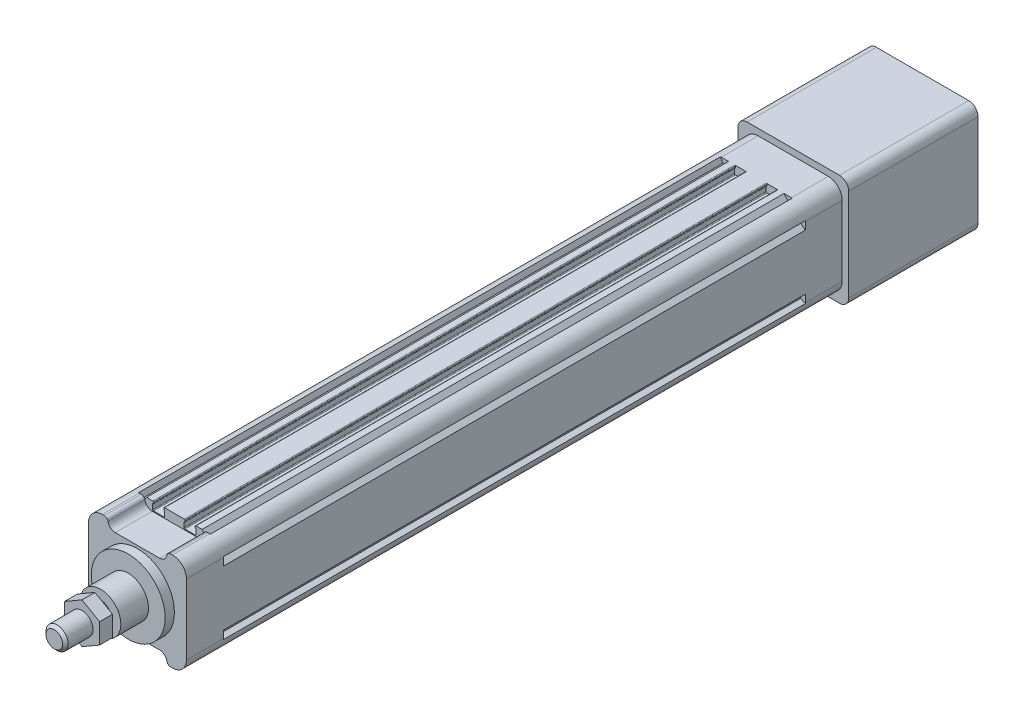
SolidWorks part; units mm, degrees
ref_plane "Front" through (0, 0, 0) normal (0, 0, 1) x (1, 0, 0)
ref_plane "Top" through (0, 0, 0) normal (0, 1, 0) x (1, 0, 0)
ref_plane "Right" through (0, 0, 0) normal (1, 0, 0) x (0, 0, -1)
sketch "草图1" plane through (0, 0, 0) normal (0, 0, 1) x (1, 0, 0)
  line L0 (19.7737, 3) -> (23.3, 3)
  line L1 (23.3, 3) -> (23.3, -3)
  line L2 (23.3, -3) -> (19.7737, -3)
  line L3 (-19.7737, -3) -> (-23.3, -3)
  line L4 (-23.3, -3) -> (-23.3, 3)
  line L5 (-23.3, 3) -> (-19.7737, 3)
  line L6 (-18.2, 24) -> (-19.4434, 26.4869)
  line L7 (-26.4869, 19.4434) -> (-24, 18.2)
  line L8 (-24, 18.2) -> (-24, 17.1)
  line L9 (-24, 17.1) -> (-26.5, 15)
  line L10 (-26.5, 15) -> (-26.5, -15)
  line L11 (-26.5, -15) -> (-24, -17.1)
  line L12 (-24, -17.1) -> (-24, -18.2)
  line L13 (-24, -18.2) -> (-26.4869, -19.4434)
  line L14 (-19.4434, -26.4869) -> (-18.2, -24)
  line L15 (-18.2, -24) -> (-17.1, -24)
  line L16 (-17.1, -24) -> (-15, -26.5)
  line L17 (-15, -26.5) -> (-11.65, -26.5)
  line L18 (-11.25, -26.1) -> (-11.25, -25.6)
  line L19 (-11.65, -25.2) -> (-11.75, -25.2)
  line L20 (-11.75, -25.2) -> (-11.75, -22.4)
  line L21 (-11.35, -22) -> (-5.65, -22)
  line L22 (-5.25, -22.4) -> (-5.25, -25.2)
  line L23 (-5.25, -25.2) -> (-5.35, -25.2)
  line L24 (-5.75, -25.6) -> (-5.75, -26.1)
  line L25 (-5.35, -26.5) -> (5.35, -26.5)
  line L26 (5.75, -26.1) -> (5.75, -25.6)
  line L27 (5.35, -25.2) -> (5.25, -25.2)
  line L28 (5.25, -25.2) -> (5.25, -22.4)
  line L29 (5.65, -22) -> (11.35, -22)
  line L30 (11.75, -22.4) -> (11.75, -25.2)
  line L31 (11.75, -25.2) -> (11.65, -25.2)
  line L32 (11.25, -25.6) -> (11.25, -26.1)
  line L33 (11.65, -26.5) -> (15, -26.5)
  line L34 (15, -26.5) -> (17.1, -24)
  line L35 (17.1, -24) -> (18.2, -24)
  line L36 (18.2, -24) -> (19.4434, -26.4869)
  line L37 (26.4869, -19.4434) -> (24, -18.2)
  line L38 (24, -18.2) -> (24, -17.1)
  line L39 (24, -17.1) -> (26.5, -15)
  line L40 (26.5, -15) -> (26.5, 15)
  line L41 (26.5, 15) -> (24, 17.1)
  line L42 (24, 17.1) -> (24, 18.2)
  line L43 (24, 18.2) -> (26.4869, 19.4434)
  line L44 (19.4434, 26.4869) -> (18.2, 24)
  line L45 (18.2, 24) -> (17.1, 24)
  line L46 (17.1, 24) -> (15, 26.5)
  line L47 (15, 26.5) -> (11.65, 26.5)
  line L48 (11.25, 26.1) -> (11.25, 25.6)
  line L49 (11.65, 25.2) -> (11.75, 25.2)
  line L50 (11.75, 25.2) -> (11.75, 22.4)
  line L51 (11.35, 22) -> (5.65, 22)
  line L52 (5.25, 22.4) -> (5.25, 25.2)
  line L53 (5.25, 25.2) -> (5.35, 25.2)
  line L54 (5.75, 25.6) -> (5.75, 26.1)
  line L55 (5.35, 26.5) -> (-5.35, 26.5)
  line L56 (-5.75, 26.1) -> (-5.75, 25.6)
  line L57 (-5.35, 25.2) -> (-5.25, 25.2)
  line L58 (-5.25, 25.2) -> (-5.25, 22.4)
  line L59 (-5.65, 22) -> (-11.35, 22)
  line L60 (-11.75, 22.4) -> (-11.75, 25.2)
  line L61 (-11.75, 25.2) -> (-11.65, 25.2)
  line L62 (-11.25, 25.6) -> (-11.25, 26.1)
  line L63 (-11.65, 26.5) -> (-15, 26.5)
  line L64 (-15, 26.5) -> (-17.1, 24)
  line L65 (-17.1, 24) -> (-18.2, 24)
  arc A0 (19.7737, 3) -> (-19.7737, 3) centre (0, 0) ccw
  arc A1 (-19.7737, -3) -> (19.7737, -3) centre (0, 0) ccw
  circle A2 centre (19, 19) radius 2.1
  circle A3 centre (19, -19) radius 2.1
  circle A4 centre (-19, -19) radius 2.1
  circle A5 centre (-19, 19) radius 2.1
  arc A6 (-19.4434, 26.4869) -> (-26.4869, 19.4434) centre (-19, 19) ccw
  arc A7 (-26.4869, -19.4434) -> (-19.4434, -26.4869) centre (-19, -19) ccw
  arc A8 (-11.65, -26.5) -> (-11.25, -26.1) centre (-11.65, -26.1) ccw
  arc A9 (-11.25, -25.6) -> (-11.65, -25.2) centre (-11.65, -25.6) ccw
  arc A10 (-11.35, -22) -> (-11.75, -22.4) centre (-11.35, -22.4) ccw
  arc A11 (-5.25, -22.4) -> (-5.65, -22) centre (-5.65, -22.4) ccw
  arc A12 (-5.35, -25.2) -> (-5.75, -25.6) centre (-5.35, -25.6) ccw
  arc A13 (-5.75, -26.1) -> (-5.35, -26.5) centre (-5.35, -26.1) ccw
  arc A14 (5.35, -26.5) -> (5.75, -26.1) centre (5.35, -26.1) ccw
  arc A15 (5.75, -25.6) -> (5.35, -25.2) centre (5.35, -25.6) ccw
  arc A16 (5.65, -22) -> (5.25, -22.4) centre (5.65, -22.4) ccw
  arc A17 (11.75, -22.4) -> (11.35, -22) centre (11.35, -22.4) ccw
  arc A18 (11.65, -25.2) -> (11.25, -25.6) centre (11.65, -25.6) ccw
  arc A19 (11.25, -26.1) -> (11.65, -26.5) centre (11.65, -26.1) ccw
  arc A20 (19.4434, -26.4869) -> (26.4869, -19.4434) centre (19, -19) ccw
  arc A21 (26.4869, 19.4434) -> (19.4434, 26.4869) centre (19, 19) ccw
  arc A22 (11.65, 26.5) -> (11.25, 26.1) centre (11.65, 26.1) ccw
  arc A23 (11.25, 25.6) -> (11.65, 25.2) centre (11.65, 25.6) ccw
  arc A24 (11.35, 22) -> (11.75, 22.4) centre (11.35, 22.4) ccw
  arc A25 (5.25, 22.4) -> (5.65, 22) centre (5.65, 22.4) ccw
  arc A26 (5.35, 25.2) -> (5.75, 25.6) centre (5.35, 25.6) ccw
  arc A27 (5.75, 26.1) -> (5.35, 26.5) centre (5.35, 26.1) ccw
  arc A28 (-5.35, 26.5) -> (-5.75, 26.1) centre (-5.35, 26.1) ccw
  arc A29 (-5.75, 25.6) -> (-5.35, 25.2) centre (-5.35, 25.6) ccw
  arc A30 (-5.65, 22) -> (-5.25, 22.4) centre (-5.65, 22.4) ccw
  arc A31 (-11.75, 22.4) -> (-11.35, 22) centre (-11.35, 22.4) ccw
  arc A32 (-11.65, 25.2) -> (-11.25, 25.6) centre (-11.65, 25.6) ccw
  arc A33 (-11.25, 26.1) -> (-11.65, 26.5) centre (-11.65, 26.1) ccw
extrude "凸台-拉伸1" add sketch "草图1" along normal blind 315
sketch "草图6" plane through (0, 0, 315) normal (0, 0, 1) x (1, 0, 0)
  line L0 (0, 0) -> (19, 0) construction
  line L2 (-26.5, -19) -> (-26.5, 19)
  line L3 (-19, 26.5) -> (-17.9161, 26.5)
  line L4 (26.5, -19) -> (26.5, 19)
  line L5 (-26.5, -26.5) -> (26.5, 26.5) construction
  line L6 (-26.5, 26.5) -> (26.5, -26.5) construction
  line L7 (-12, 21.5) -> (12, 21.5)
  line L9 (19, 26.5) -> (17.9161, 26.5)
  line L10 (19, -26.5) -> (17.9161, -26.5)
  line L11 (-12, -21.5) -> (12, -21.5)
  line L12 (-19, -26.5) -> (-17.9161, -26.5)
  arc A0 (12, 21.5) -> (15.9441, 24.8333) centre (12, 25.5) ccw
  arc A1 (-15.9441, 24.8333) -> (-12, 21.5) centre (-12, 25.5) ccw
  arc A2 (-15.9441, 24.8333) -> (-17.9161, 26.5) centre (-17.9161, 24.5) ccw
  arc A3 (15.9441, 24.8333) -> (17.9161, 26.5) centre (17.9161, 24.5) cw
  arc A4 (-26.5, -19) -> (-19, -26.5) centre (-19, -19) ccw
  arc A5 (19, -26.5) -> (26.5, -19) centre (19, -19) ccw
  arc A6 (26.5, 19) -> (19, 26.5) centre (19, 19) ccw
  arc A7 (-26.5, 19) -> (-19, 26.5) centre (-19, 19) cw
  arc A8 (15.9441, -24.8333) -> (17.9161, -26.5) centre (17.9161, -24.5) ccw
  arc A9 (12, -21.5) -> (15.9441, -24.8333) centre (12, -25.5) cw
  arc A10 (-15.9441, -24.8333) -> (-12, -21.5) centre (-12, -25.5) cw
  arc A11 (-15.9441, -24.8333) -> (-17.9161, -26.5) centre (-17.9161, -24.5) cw
  point P0 (0, 0)
  point P9 (0, 21.5)
  point P13 (20, 20.8461)
  point P16 (-12, 20.8461)
  dimension "D5" = 4
  dimension "D6" = 2
  dimension "D7" = 2
  dimension "D9" = 7.5
  dimension "D1" = 53
  dimension "D2" = 53
  dimension "D3" = 26.5
  dimension "D4" = 24
  dimension "D8" = 5
extrude "凸台-拉伸2" add sketch "草图6" along normal blind 20
sketch "草图7" plane through (0, 0, 335) normal (0, 0, 1) x (1, 0, 0)
  circle A0 centre (0, 0) radius 20
  dimension "D1" = 40
extrude "凸台-拉伸3" add sketch "草图7" along normal blind 5
sketch "草图9" plane through (0, 0, 340) normal (0, 0, 1) x (1, 0, 0)
  circle A0 centre (0, 0) radius 11
  dimension "D1" = 22
extrude "凸台-拉伸4" add sketch "草图9" along normal blind 15
sketch "草图10" plane through (0, 0, 355) normal (0, 0, 1) x (1, 0, 0)
  circle A0 centre (0, 0) radius 6
  dimension "D1" = 12
extrude "凸台-拉伸5" add sketch "草图10" along normal blind 25
sketch "草图11" plane through (0, 0, 0) normal (0, 0, -1) x (-1, 0, 0)
  line L1 (-19, -26.5) -> (19, -26.5)
  line L2 (-26.5, -19) -> (-26.5, 19)
  line L3 (-19, 26.5) -> (19, 26.5)
  line L4 (26.5, -19) -> (26.5, 19)
  line L5 (-26.5, -26.5) -> (26.5, 26.5) construction
  line L6 (-26.5, 26.5) -> (26.5, -26.5) construction
  arc A0 (-26.5, -19) -> (-19, -26.5) centre (-19, -19) ccw
  arc A1 (19, -26.5) -> (26.5, -19) centre (19, -19) ccw
  arc A2 (26.5, 19) -> (19, 26.5) centre (19, 19) ccw
  arc A3 (-26.5, 19) -> (-19, 26.5) centre (-19, 19) cw
  point P0 (0, 0)
  dimension "D3" = 7.5
  dimension "D1" = 53
  dimension "D2" = 53
extrude "凸台-拉伸6" add sketch "草图11" along normal blind 20
sketch "草图12" plane through (0, 0, -20) normal (0, 0, -1) x (-1, 0, 0)
  line L1 (-25, -30) -> (25, -30)
  line L2 (-30, -25) -> (-30, 25)
  line L3 (-25, 30) -> (25, 30)
  line L4 (30, -25) -> (30, 25)
  line L5 (-30, -30) -> (30, 30) construction
  line L6 (-30, 30) -> (30, -30) construction
  arc A0 (-30, -25) -> (-25, -30) centre (-25, -25) ccw
  arc A1 (25, -30) -> (30, -25) centre (25, -25) ccw
  arc A2 (30, 25) -> (25, 30) centre (25, 25) ccw
  arc A3 (-30, 25) -> (-25, 30) centre (-25, 25) cw
  point P0 (0, 0)
  dimension "D3" = 5
  dimension "D1" = 60
  dimension "D2" = 60
extrude "凸台-拉伸7" add sketch "草图12" along normal blind 70
sketch "草图14" plane through (0, 0, -90) normal (0, 0, -1) x (-1, 0, 0)
  circle A0 centre (0, 0) radius 19
  dimension "D1" = 38
extrude "切除-拉伸2" cut sketch "草图14" against normal blind 70
hole_wizard "M6 螺纹孔1" positions "草图15" profile "草图16" tap size "M6" standard "GB"
sketch "草图15" plane through (-26.5, 0, 0) normal (-1, 0, 0) x (0, 0, 1)
  line L0 (-20, -25) -> (-20, 25) construction
  line L1 (335, 19) -> (335, -19) construction
  point P0 (325, 11)
  point P2 (325, -11)
  point P4 (-10, 11)
  point P6 (-10, -11)
  dimension "D1" = 10
  dimension "D2" = 10
  dimension "D3" = 11
  dimension "D4" = 11
  dimension "D5" = 10
  dimension "D6" = 10
  dimension "D7" = 22
  dimension "D8" = 11
sketch "草图16" plane through (-26.5, 11, 325) normal (0, 1, 0) x (0, 0, 1)
  line L0 (0, 0) -> (0, 16.5022)
  line L1 (0, 16.5022) -> (2.5, 15)
  line L2 (2.5, 15) -> (2.5, 0)
  line L5 (2.5, 0) -> (0, 0)
  line L10 (0, 16.5022) -> (-2.5, 15) construction
  line L11 (0, -6.35) -> (0, 107.95) construction
  dimension "螺纹孔钻头直径" = 5
  dimension "螺纹孔钻头深度" = 15
  dimension "导头角度" = 118
cosmetic thread "孔螺蚊线4" parameters "D1"=12, "D2"=6
cosmetic thread "孔螺蚊线5" parameters "D1"=12, "D2"=6
cosmetic thread "孔螺蚊线6" parameters "D1"=12, "D2"=6
cosmetic thread "孔螺蚊线7" parameters "D1"=12, "D2"=6
chamfer "倒角1" distance 1.5 angle 45 1 edges at (6, 0, 380)
sketch "草图17" plane through (0, 0, 355) normal (0, 0, 1) x (1, 0, 0)
  line L1 (0, 10.9697) -> (-9.5, 5.4848)
  line L2 (-9.5, 5.4848) -> (-9.5, -5.4848)
  line L3 (-9.5, -5.4848) -> (0, -10.9697)
  line L4 (0, -10.9697) -> (9.5, -5.4848)
  line L5 (9.5, -5.4848) -> (9.5, 5.4848)
  line L6 (9.5, 5.4848) -> (0, 10.9697)
  circle A0 centre (0, 0) radius 9.5 construction
  dimension "D1" = 19
extrude "凸台-拉伸8" add sketch "草图17" along normal blind 7 from offset 3
